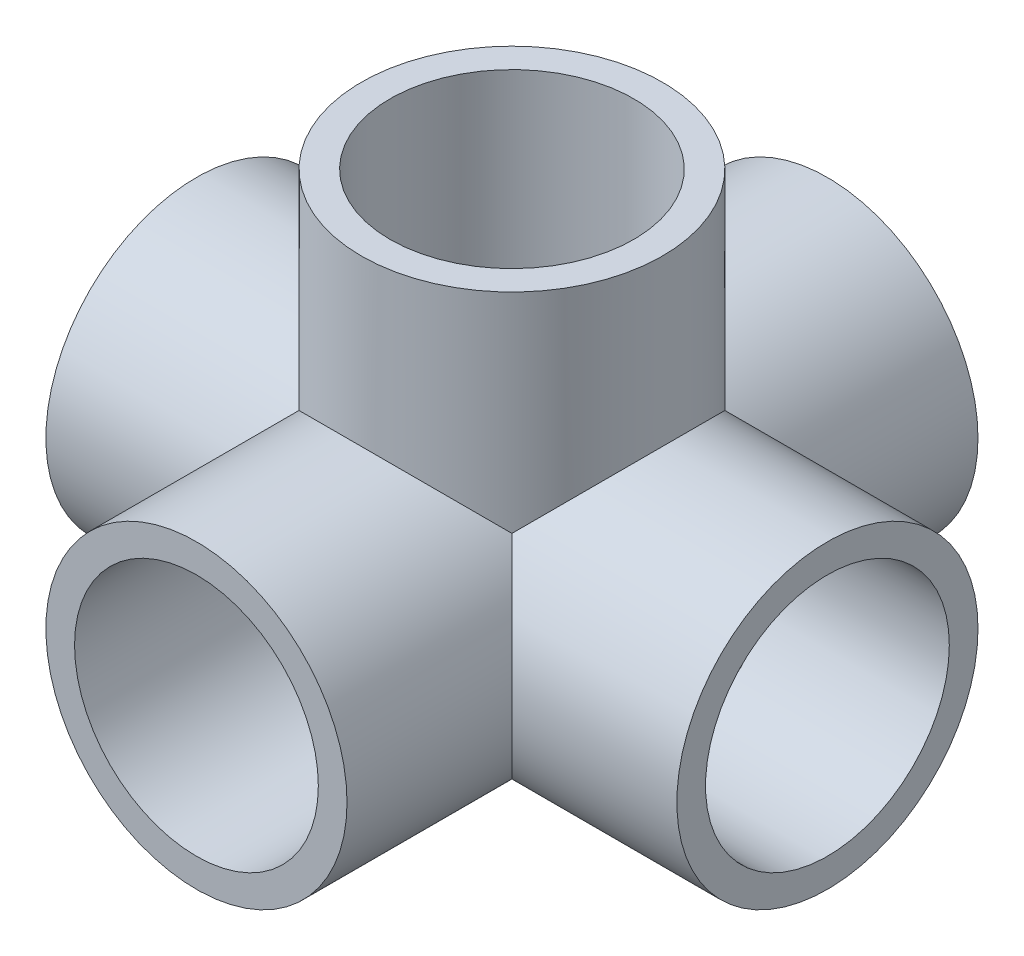
SolidWorks part; units mm, degrees
ref_plane "Front Plane" through (0, 0, 0) normal (0, 0, 1) x (1, 0, 0)
ref_plane "Top Plane" through (0, 0, 0) normal (0, 1, 0) x (1, 0, 0)
ref_plane "Right Plane" through (0, 0, 0) normal (1, 0, 0) x (0, 0, -1)
sketch "Sketch1" plane through (0, 0, 0) normal (0, 0, 1) x (1, 0, 0)
  circle A0 centre (0, 0) radius 16.6687
  dimension "D1" = 33.3375
extrude "Boss-Extrude1" add sketch "Sketch1" along normal blind 69.85 contours A0
sketch "Sketch3" plane through (0, 0, 69.85) normal (0, 0, 1) x (1, 0, 0)
  circle A0 centre (0, 0) radius 13.4938
  dimension "D1" = 26.9875
extrude "Cut-Extrude1" cut sketch "Sketch3" against normal blind 26.9875 and the other way through all
sketch "Sketch4" plane through (0, 0, 0) normal (1, 0, 0) x (0, 0, -1)
  line L0 (-69.85, 16.6687) -> (-69.85, -16.6687) construction
  circle A0 centre (-34.925, 0) radius 16.6687
  dimension "D1" = 33.3375
  dimension "D2" = 34.925
extrude "Boss-Extrude2" add sketch "Sketch4" along normal mid plane 69.85
sketch "Sketch5" plane through (34.925, 0, 0) normal (1, 0, 0) x (0, 0, -1)
  circle A0 centre (-34.925, 0) radius 12.7
  dimension "D1" = 25.4
extrude "Cut-Extrude2" cut sketch "Sketch5" against normal through all
sketch "Sketch11" plane through (0, 0, 0) normal (0, 0, 1) x (1, 0, 0)
  circle A0 centre (0, 0) radius 13.4938
  dimension "D1" = 26.9875
extrude "Cut-Extrude8" cut sketch "Sketch11" along normal blind 19.05
sketch "Sketch10" plane through (0, 0, 69.85) normal (0, 0, 1) x (1, 0, 0)
  circle A0 centre (0, 0) radius 12.7
  dimension "D1" = 25.4
extrude "Cut-Extrude5" cut sketch "Sketch10" against normal through all both and the other way through all
sketch "Sketch13" plane through (34.925, 0, 0) normal (1, 0, 0) x (0, 0, -1)
  circle A0 centre (-34.925, 0) radius 13.4937
  dimension "D1" = 26.9875
extrude "Cut-Extrude9" cut sketch "Sketch13" against normal blind 19.05
sketch "Sketch14" plane through (-34.925, 0, 0) normal (-1, 0, 0) x (0, 0, 1)
  circle A0 centre (34.925, 0) radius 13.4937
  dimension "D1" = 26.9875
extrude "Cut-Extrude10" cut sketch "Sketch14" against normal blind 19.05
sketch "Sketch15" plane through (0, 0, 0) normal (0, 1, 0) x (1, 0, 0)
  circle A0 centre (0, -34.925) radius 16.6687
  dimension "D1" = 33.3375
extrude "Boss-Extrude3" add sketch "Sketch15" along normal blind 34.925
sketch "Sketch17" plane through (0, 34.925, 0) normal (0, 1, 0) x (1, 0, 0)
  circle A0 centre (0, -34.925) radius 13.4938
  dimension "D1" = 26.9875
extrude "Cut-Extrude12" cut sketch "Sketch17" against normal blind 19.05
sketch "Sketch19" plane through (34.925, 0, 0) normal (1, 0, 0) x (0, 0, -1)
  circle A0 centre (-34.925, 0) radius 12.7
extrude "Cut-Extrude14" cut sketch "Sketch19" against normal through all
sketch "Sketch20" plane through (0, 0, 69.85) normal (0, 0, 1) x (1, 0, 0)
  circle A0 centre (0, 0) radius 12.7
extrude "Cut-Extrude15" cut sketch "Sketch20" against normal through all
sketch "Sketch22" plane through (0, 34.925, 0) normal (0, 1, 0) x (1, 0, 0)
  circle A0 centre (0, -34.925) radius 12.7
  dimension "D1" = 25.4
extrude "Cut-Extrude16" cut sketch "Sketch22" against normal blind 30.48
